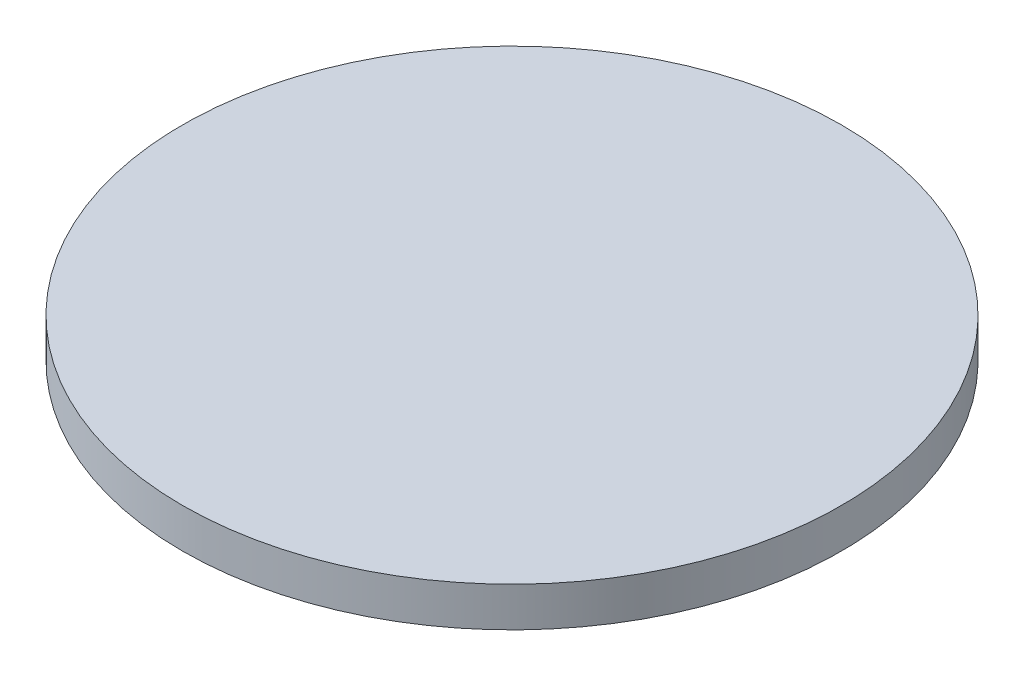
SolidWorks part; units mm, degrees
ref_plane "Front Plane" through (0, 0, 0) normal (0, 0, 1) x (1, 0, 0)
ref_plane "Top Plane" through (0, 0, 0) normal (0, 1, 0) x (1, 0, 0)
ref_plane "Right Plane" through (0, 0, 0) normal (1, 0, 0) x (0, 0, -1)
sketch "Sketch1" plane through (0, 0, 0) normal (0, 1, 0) x (1, 0, 0)
  circle A0 centre (0, 0) radius 25
  dimension "D1" = 50
extrude "Boss-Extrude1" add sketch "Sketch1" along normal blind 3
